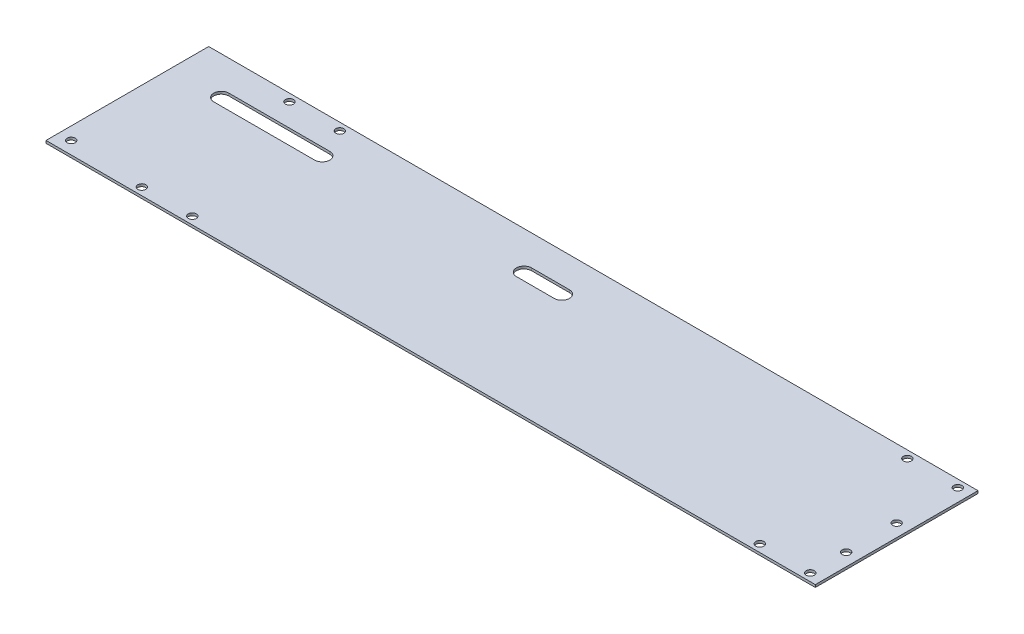
SolidWorks part; units mm, degrees
ref_plane "前视基准面" through (0, 0, 0) normal (0, 0, 1) x (1, 0, 0)
ref_plane "上视基准面" through (0, 0, 0) normal (0, 1, 0) x (1, 0, 0)
ref_plane "右视基准面" through (0, 0, 0) normal (1, 0, 0) x (0, 0, -1)
sketch "草图1" plane through (0, 0, 0) normal (0, 1, 0) x (1, 0, 0)
  line L1 (0, 0) -> (330, 0)
  line L2 (0, 0) -> (0, 64.5)
  line L3 (0, 64.5) -> (330, 64.5)
  line L4 (330, 0) -> (330, 64.5)
  dimension "D1" = 64.5
  dimension "D2" = 330
extrude "凸台-拉伸1" add sketch "草图1" along normal blind 1
sketch "草图2" plane through (0, 1, 0) normal (0, 1, 0) x (1, 0, 0)
  line L0 (35, 61.5) -> (55, 61.5) construction
  line L1 (280, 61.5) -> (300, 61.5) construction
  line L2 (330, 64.5) -> (0, 64.5) construction
  line L3 (0, 64.5) -> (0, 0) construction
  line L4 (330, 0) -> (330, 64.5) construction
  line L5 (0, 32.25) -> (330, 32.25) construction
  line L6 (280, 3) -> (300, 3) construction
  line L7 (35, 3) -> (55, 3) construction
  line L8 (300, 17.25) -> (300, 37.25) construction
  line L9 (0, 0) -> (330, 0) construction
  circle A0 centre (35, 61.5) radius 1.6
  circle A1 centre (55, 61.5) radius 1.6
  circle A2 centre (280, 61.5) radius 1.6
  circle A3 centre (300, 61.5) radius 1.6
  circle A4 centre (300, 3) radius 1.6
  circle A5 centre (280, 3) radius 1.6
  circle A6 centre (55, 3) radius 1.6
  circle A7 centre (35, 3) radius 1.6
  circle A8 centre (300, 37.25) radius 1.6
  circle A9 centre (300, 17.25) radius 1.6
  circle A10 centre (5, 5) radius 1.6
  dimension "D2" = 3.2
  dimension "D4" = 35
  dimension "D5" = 30
  dimension "D1" = 20
  dimension "D3" = 3
  dimension "D6" = 5
  dimension "D7" = 5
  dimension "D8" = 5
extrude "切除-拉伸1" cut sketch "草图2" against normal through all
sketch "草图3" plane through (0, 1, 0) normal (0, 1, 0) x (1, 0, 0)
  line L0 (0, 0) -> (330, 0) construction
  line L1 (330, 64.5) -> (305, 64.5)
  line L2 (330, 64.5) -> (330, 0)
  line L3 (330, 0) -> (305, 0)
  line L4 (305, 64.5) -> (305, 0)
  dimension "D1" = 25
extrude "切除-拉伸2" cut sketch "草图3" against normal up to next
sketch "草图4" plane through (0, 1, 0) normal (0, 1, 0) x (1, 0, 0)
  line L0 (140, 49.5) -> (155, 49.5) construction
  line L1 (140, 52.5) -> (155, 52.5)
  line L2 (140, 46.5) -> (155, 46.5)
  line L3 (0, 64.5) -> (0, 0) construction
  line L4 (305, 64.5) -> (0, 64.5) construction
  line L5 (20, 49.5) -> (60, 49.5) construction
  line L6 (20, 52.5) -> (60, 52.5)
  line L7 (20, 46.5) -> (60, 46.5)
  arc A0 (140, 52.5) -> (140, 46.5) centre (140, 49.5) ccw
  arc A1 (155, 46.5) -> (155, 52.5) centre (155, 49.5) ccw
  arc A2 (20, 52.5) -> (20, 46.5) centre (20, 49.5) ccw
  arc A3 (60, 46.5) -> (60, 52.5) centre (60, 49.5) ccw
  point P2 (147.5, 49.5)
  point P13 (40, 49.5)
  dimension "D1" = 6
  dimension "D2" = 155
  dimension "D3" = 140
  dimension "D4" = 15
  dimension "D5" = 20
  dimension "D6" = 60
extrude "切除-拉伸3" cut sketch "草图4" against normal up to next
